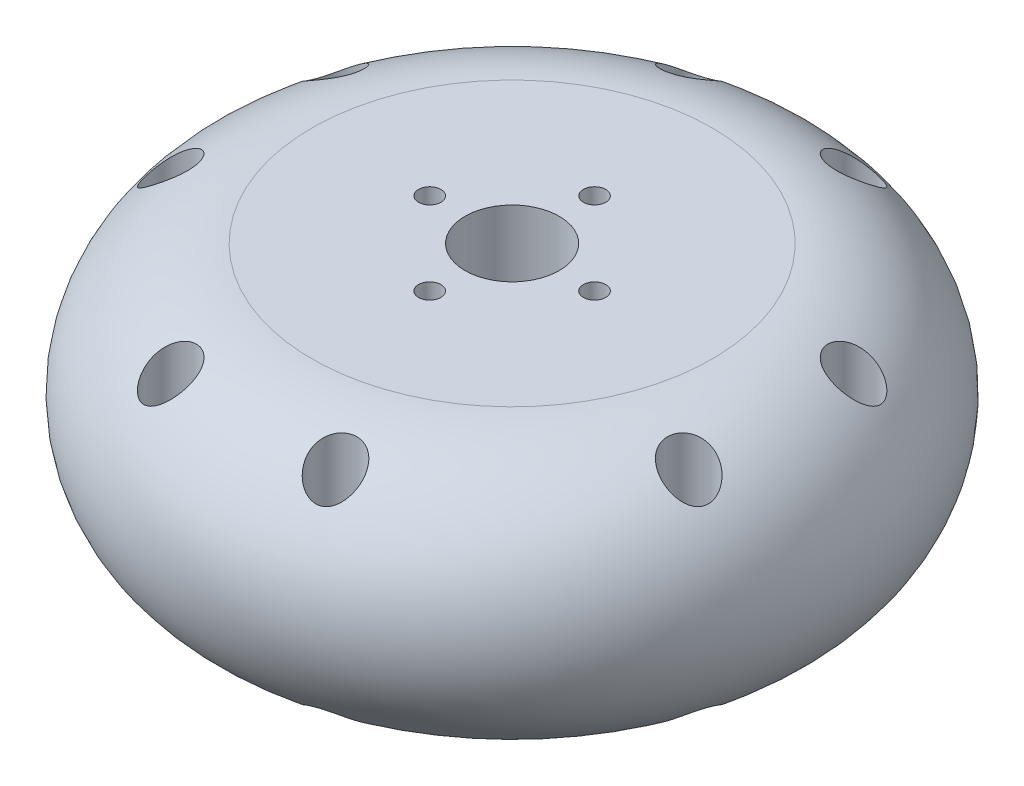
SolidWorks part; units mm, degrees
ref_plane "Front Plane" through (0, 0, 0) normal (0, 0, 1) x (1, 0, 0)
ref_plane "Top Plane" through (0, 0, 0) normal (0, 1, 0) x (1, 0, 0)
ref_plane "Right Plane" through (0, 0, 0) normal (1, 0, 0) x (0, 0, -1)
sketch "Sketch1" plane through (0, 0, 0) normal (0, 0, 1) x (1, 0, 0)
  line L0 (0, 0) -> (-17, 0)
  line L1 (-17, -22) -> (0, -22)
  line L2 (0, -22) -> (0, 0) construction
  line L3 (0, -22) -> (0, 0)
  arc A0 (-17, 0) -> (-17, -22) centre (-17, -11) ccw
  point P5 (-28, -11)
  dimension "D1" = 22
  dimension "D2" = 17
revolve "Revolve2" add sketch "Sketch1" angle 360 about L2
sketch "Sketch2" plane through (0, 0, 0) normal (0, 1, 0) x (1, 0, 0)
  line L0 (0, 0) -> (0, 28) construction
  circle A0 centre (7, 22) radius 2
  circle A1 centre (-7, 22) radius 2
  circle A2 centre (0, 0) radius 28 construction
  dimension "D1" = 4
  dimension "D2" = 7
  dimension "D3" = 7
  dimension "D4" = 22
extrude "Cut-Extrude1" cut sketch "Sketch2" against normal through all
pattern_circular "CirPattern1" count 4 over 360 about axis through (0, 0, 0) along (0, 1, 0) of "Cut-Extrude1"
sketch "Sketch3" plane through (0, 0, 0) normal (0, 1, 0) x (1, 0, 0)
  circle A0 centre (7, 0) radius 0.95
  dimension "D2" = 1.9
  dimension "D1" = 7
extrude "Cut-Extrude2" cut sketch "Sketch3" against normal blind 5
pattern_circular "CirPattern2" count 4 over 360 about axis through (0, 0, 0) along (0, 1, 0) of "Cut-Extrude2"
sketch "Sketch4" plane through (0, 0, 0) normal (0, 1, 0) x (1, 0, 0)
  circle A0 centre (0, 0) radius 4
  dimension "D1" = 8
extrude "Cut-Extrude3" cut sketch "Sketch4" against normal through all
